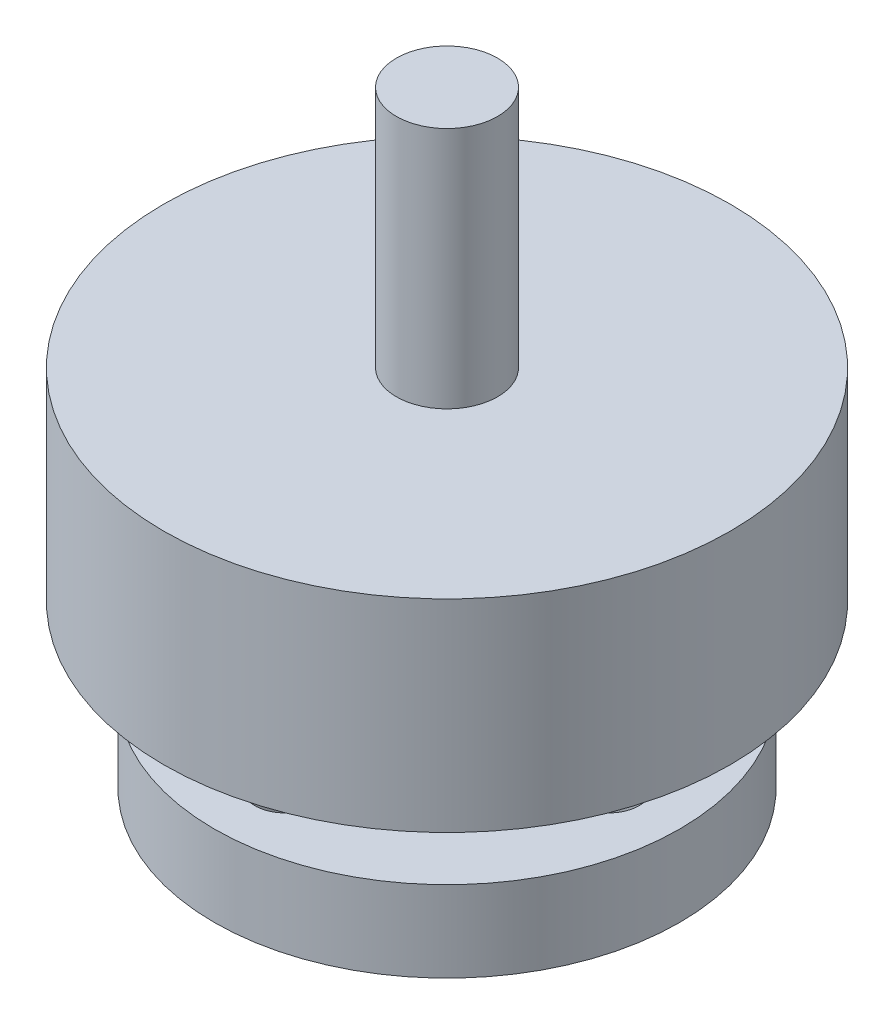
SolidWorks part; units mm, degrees
material "Custom Plastic"
ref_plane "Front Plane" through (0, 0, 0) normal (0, 0, 1) x (1, 0, 0)
ref_plane "Top Plane" through (0, 0, 0) normal (0, 1, 0) x (1, 0, 0)
ref_plane "Right Plane" through (0, 0, 0) normal (1, 0, 0) x (0, 0, -1)
sketch "Sketch1" plane through (0, 0, 0) normal (0, 0, 1) x (1, 0, 0)
  line L0 (0, 0) -> (0, 30) construction
  line L1 (0, 30) -> (2.5, 30)
  line L2 (2.5, 30) -> (2.5, 18)
  line L3 (2.5, 18) -> (14, 18)
  line L4 (14, 18) -> (14, 8)
  line L5 (14, 8) -> (5.5, 8)
  line L6 (5.5, 8) -> (5.5, 4)
  line L7 (5.5, 4) -> (11.5, 4)
  line L8 (11.5, 4) -> (11.5, 0)
  line L9 (11.5, 0) -> (0, 0)
  line L10 (0, 0) -> (0, 30)
  dimension "D1" = 2.5
  dimension "D2" = 12
  dimension "D3" = 30
  dimension "D4" = 4
  dimension "D5" = 4
  dimension "D6" = 14
  dimension "D7" = 11.5
  dimension "D8" = 5.5
revolve "Revolve1" add sketch "Sketch1" angle 360 about L0
sketch "Sketch2" plane through (0, 0, 0) normal (0, -1, 0) x (1, 0, 0)
  line L0 (0, 8) -> (0, -8) construction
  line L1 (8, 0) -> (-8, 0) construction
  circle A0 centre (0, 8) radius 1.5
  circle A1 centre (8, 0) radius 1.5
  circle A2 centre (0, -8) radius 1.5
  circle A3 centre (-8, 0) radius 1.5
  point P4 (0, 0)
  point P8 (0, 0)
  dimension "D2" = 3
  dimension "D1" = 16
extrude "Cut-Extrude1" cut sketch "Sketch2" against normal blind 4
sketch "Sketch3" plane through (0, 0, 0) normal (0, -1, 0) x (1, 0, 0)
  line L0 (0, 6.5) -> (0, 9.5) construction
  line L1 (0, -9.5) -> (0, -6.5) construction
  line L2 (6.5, 0) -> (9.5, 0) construction
  line L3 (-9.5, 0) -> (-6.5, 0) construction
  circle A1 centre (0, -8) radius 1.5
  circle A2 centre (0, -8) radius 1.5 construction
  circle A3 centre (8, 0) radius 1.5
  circle A4 centre (8, 0) radius 1.5 construction
  circle A5 centre (0, 8) radius 1.5
  circle A6 centre (0, 8) radius 1.5 construction
  circle A7 centre (-8, 0) radius 1.5
  circle A8 centre (-8, 0) radius 1.5 construction
  dimension "D1" = 0
  dimension "D2" = 0
  dimension "D3" = 0
  dimension "D4" = 0
